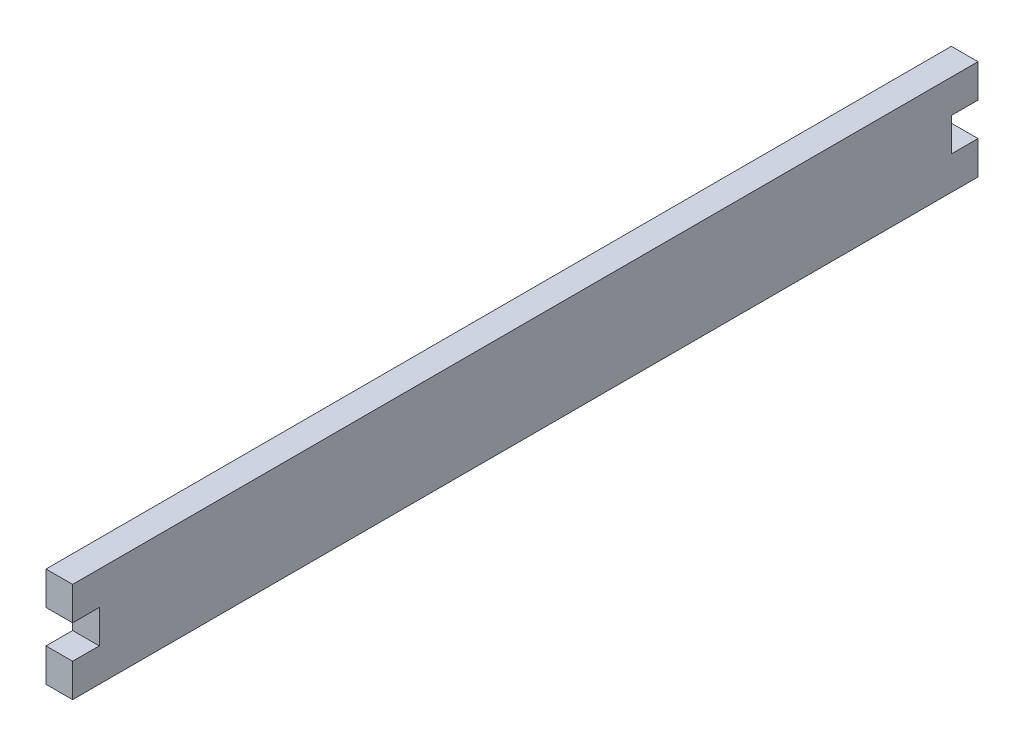
SolidWorks part; units mm, degrees
ref_plane "Front Plane" through (0, 0, 0) normal (0, 0, 1) x (1, 0, 0)
ref_plane "Top Plane" through (0, 0, 0) normal (0, 1, 0) x (1, 0, 0)
ref_plane "Right Plane" through (0, 0, 0) normal (1, 0, 0) x (0, 0, -1)
sketch "Sketch1" plane through (0, 0, 0) normal (1, 0, 0) x (0, 0, -1)
  line L0 (0, 7.9375) -> (0, 11.9062)
  line L1 (0, 0) -> (107.95, 0)
  line L2 (0, 0) -> (0, 3.9688)
  line L3 (0, 11.9062) -> (107.95, 11.9062)
  line L4 (107.95, 0) -> (107.95, 3.9688)
  line L5 (0, 7.9375) -> (3.175, 7.9375)
  line L6 (53.975, 11.9062) -> (53.975, 0) construction
  line L7 (0, 3.9688) -> (3.175, 3.9688)
  line L8 (3.175, 7.9375) -> (3.175, 3.9688)
  line L9 (104.775, 7.9375) -> (104.775, 3.9688)
  line L10 (107.95, 3.9688) -> (104.775, 3.9688)
  line L11 (107.95, 7.9375) -> (104.775, 7.9375)
  line L12 (107.95, 7.9375) -> (107.95, 11.9062)
  dimension "D1" = 11.9062
  dimension "D2" = 107.95
  dimension "D3" = 3.175
extrude "Boss-Extrude1" add sketch "Sketch1" along normal blind 3.175
